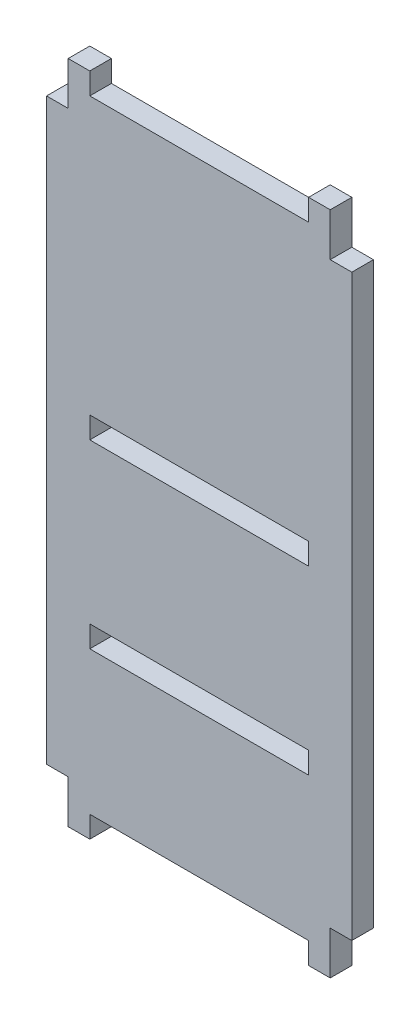
SolidWorks part; units mm, degrees
material "Acrylic (Medium-high impact)"
ref_plane "Front Plane" through (0, 0, 0) normal (0, 0, 1) x (1, 0, 0)
ref_plane "Top Plane" through (0, 0, 0) normal (0, 1, 0) x (1, 0, 0)
ref_plane "Right Plane" through (0, 0, 0) normal (1, 0, 0) x (0, 0, -1)
sketch "Sketch1" plane through (0, 0, 0) normal (0, 0, 1) x (1, 0, 0)
  line L2 (-41.8719, 0) -> (-41.8719, 12.7)
  line L3 (-41.8719, 12.7) -> (-48.2219, 12.7)
  line L4 (-48.2219, 12.7) -> (-48.2219, 182.7727)
  line L5 (-48.2219, 182.7727) -> (-41.8719, 182.7727)
  line L6 (-41.8719, 182.7727) -> (-41.8719, 195.4727)
  line L7 (-41.8719, 0) -> (-41.8719, 195.4727) construction
  line L8 (-35.5219, 195.4727) -> (-41.8719, 195.4727) construction
  line L9 (-41.8719, 195.4727) -> (-35.5219, 195.4727)
  line L10 (-35.5219, 195.4727) -> (-35.5219, 189.1227)
  line L11 (-35.5219, 189.1227) -> (28.7655, 189.1227)
  line L12 (28.7655, 189.1227) -> (28.7655, 195.4727)
  line L13 (28.7655, 195.4727) -> (35.1155, 195.4727)
  line L14 (35.1155, 195.4727) -> (35.1155, 182.7727)
  line L15 (35.1155, 182.7727) -> (41.4655, 182.7727)
  line L16 (41.4655, 182.7727) -> (41.4655, 12.7)
  line L17 (41.4655, 12.7) -> (35.1155, 12.7)
  line L18 (35.1155, 0) -> (35.1155, 107.95) construction
  line L19 (35.1155, 12.7) -> (35.1155, 0)
  line L20 (35.1155, 0) -> (28.7655, 0)
  line L21 (28.7655, 0) -> (28.7655, 6.35)
  line L22 (28.7655, 6.35) -> (-35.5219, 6.35)
  line L23 (41.4655, 6.35) -> (41.4655, 0) construction
  line L24 (-35.5219, 6.35) -> (-35.5219, 0)
  line L25 (-35.5219, 0) -> (-41.8719, 0)
  line L26 (-35.5219, 48.4378) -> (28.7655, 48.4378) construction
  line L27 (28.7655, 48.4378) -> (28.7655, 54.7878) construction
  line L28 (28.7655, 54.7878) -> (-35.5219, 54.7878) construction
  line L29 (-35.5219, 54.7878) -> (-35.5219, 48.4378) construction
  line L30 (-35.5219, 101.6) -> (28.7655, 101.6) construction
  line L31 (28.7655, 101.6) -> (28.7655, 107.95) construction
  line L32 (28.7655, 107.95) -> (-35.5219, 107.95) construction
  line L33 (-35.5219, 107.95) -> (-35.5219, 101.6) construction
  line L34 (-35.5219, 48.4378) -> (28.7655, 48.4378)
  line L37 (28.7655, 48.4378) -> (28.7655, 54.7878)
  line L38 (28.7655, 54.7878) -> (-35.5219, 54.7878)
  line L39 (-35.5219, 54.7878) -> (-35.5219, 48.4378)
  line L40 (-35.5219, 101.6) -> (28.7655, 101.6)
  line L41 (28.7655, 101.6) -> (28.7655, 107.95)
  line L42 (28.7655, 107.95) -> (-35.5219, 107.95)
  line L43 (-35.5219, 107.95) -> (-35.5219, 101.6)
  line L44 (41.4655, 6.35) -> (35.1155, 6.35) construction
  dimension "D1" = 6.35
extrude "Boss-Extrude1" add sketch "Sketch1" along normal blind 6.35
sketch "Sketch2" plane through (0, 0, 6.35) normal (0, 0, 1) x (1, 0, 0)
  line L0 (-15.7861, 81.4364) -> (-15.7861, 74.9514)
  line L1 (-22.8219, 101.6) -> (-22.8219, 78.1939) construction
  line L2 (28.7655, 101.6) -> (-35.5219, 101.6) construction
  line L3 (-22.8219, 78.1939) -> (-22.8219, 54.7878) construction
  line L4 (28.7655, 54.7878) -> (-35.5219, 54.7878) construction
  line L5 (-48.2219, 182.7727) -> (-48.2219, 12.7) construction
  arc A0 (-15.7861, 81.4364) -> (-15.7861, 74.9514) centre (-22.8219, 78.1939) ccw
  dimension "D1" = 15.494
  dimension "D2" = 6.4849
  dimension "D3" = 25.4
extrude "Cut-Extrude1" [suppressed] cut sketch "Sketch2" against normal through all
